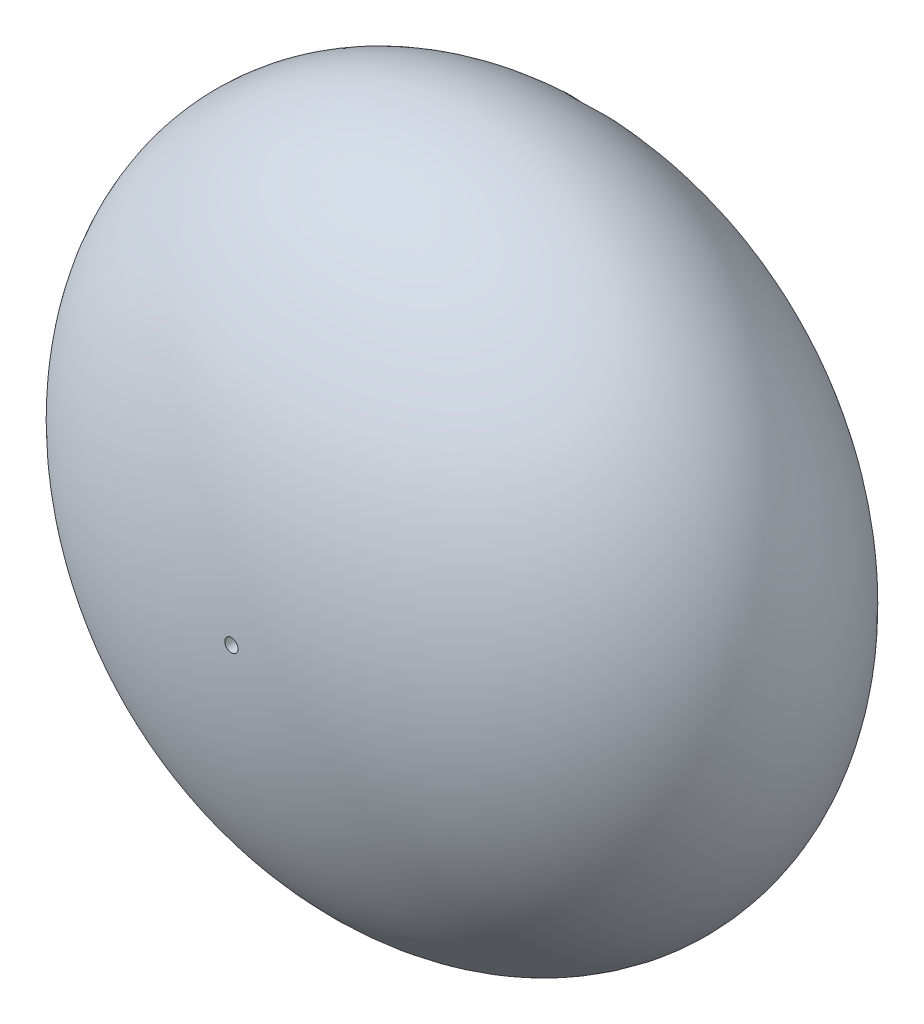
SolidWorks part; units mm, degrees
ref_plane "Front Plane" through (0, 0, 0) normal (0, 0, 1) x (1, 0, 0)
ref_plane "Top Plane" through (0, 0, 0) normal (0, 1, 0) x (1, 0, 0)
ref_plane "Right Plane" through (0, 0, 0) normal (1, 0, 0) x (0, 0, -1)
other "Center of Mass"
sketch "Sketch1" plane through (0, 0, 0) normal (0, 1, 0) x (1, 0, 0)
  line L0 (0, 17.5) -> (0, -17.5) construction
  line L1 (0, 17.5) -> (0, -17.5)
  ellipse E0 centre (0, 0) end of major axis (-26.25, 0) minor radius 17.5 (0, -17.5) -> (0, 17.5) ccw
  dimension "D1" = 17.5
  dimension "D2" = 26.25
revolve "Revolve4" add sketch "Sketch1" angle 360 about L0
sketch "Sketch3" plane through (0, 0, 0) normal (0, 0, 1) x (1, 0, 0)
  circle A0 centre (0, 0) radius 7
  point P2 (-7.0773, -7.1533)
  point P3 (0, 0)
  point P4 (0, 0)
  point P7 (0, 0)
  dimension "D1" = 14
extrude "Cut-Extrude1" cut sketch "Sketch3" along normal blind 13
sketch "Sketch4" plane through (0, 0, 0) normal (0, 0, 1) x (1, 0, 0)
  circle A0 centre (0, 0) radius 0.5
  dimension "D1" = 1
extrude "Cut-Extrude2" cut sketch "Sketch4" against normal through all both and the other way through all
sketch "Sketch5" plane through (0, 0, 0) normal (0, 1, 0) x (1, 0, 0)
  circle A0 centre (0, 10) radius 1.5
  point P2 (0, 10.3006)
  point P4 (0, 10)
  point P5 (3.5014, 9.367)
  dimension "D1" = 3
  dimension "D2" = 10
extrude "Cut-Extrude3" cut sketch "Sketch5" against normal through all both and the other way through all
